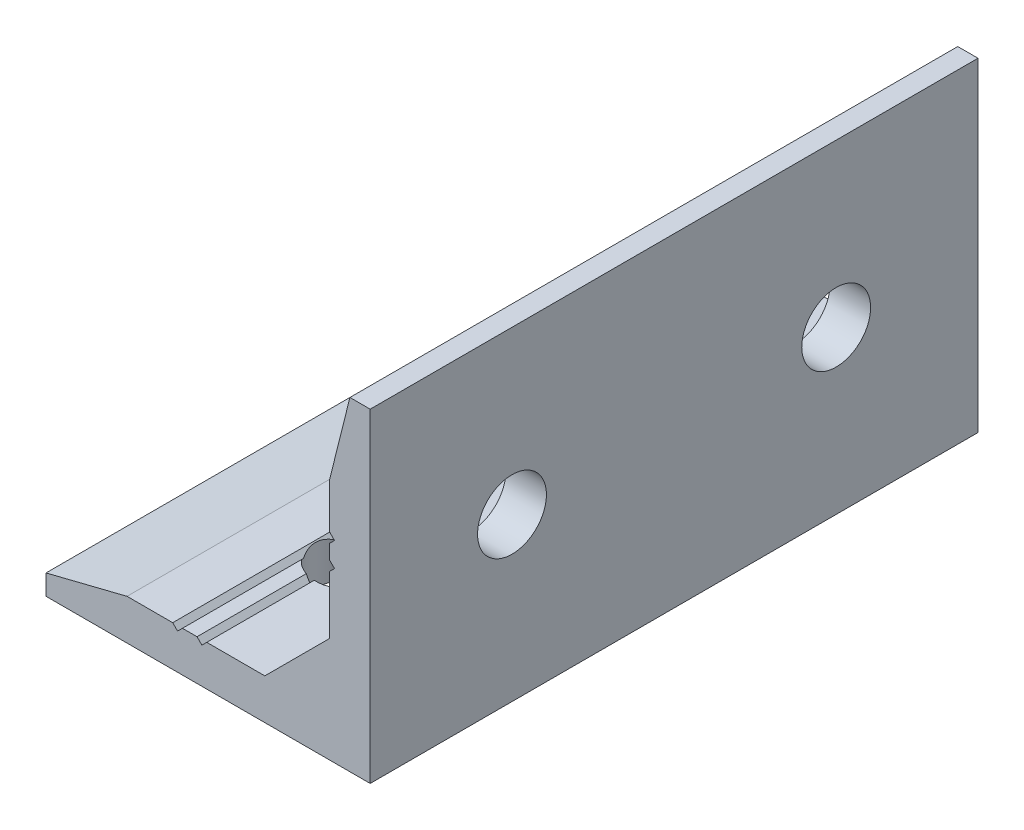
SolidWorks part; units mm, degrees
ref_plane "前视基准面" through (0, 0, 0) normal (0, 0, 1) x (1, 0, 0)
ref_plane "上视基准面" through (0, 0, 0) normal (0, 1, 0) x (1, 0, 0)
ref_plane "右视基准面" through (0, 0, 0) normal (1, 0, 0) x (0, 0, -1)
sketch "草图1" plane through (0, 0, 0) normal (0, 0, 1) x (1, 0, 0)
  line B0 (0, 0) -> (40, 0)
  line B1 (40, 0) -> (40, 40)
  line B2 (10, 5) -> (15.635, 5)
  line B3 (16.835, 5) -> (18.635, 5)
  line B4 (19.835, 5) -> (27, 5)
  line B5 (35, 13) -> (35, 20.165)
  line B6 (35, 21.365) -> (35, 23.165)
  line B7 (35, 24.365) -> (35, 30)
  line B8 (0, 2.5) -> (0, 0)
  line B9 (37.5, 40) -> (40, 40)
  line B10 (0, 2.5) -> (10, 5)
  line B11 (37.5, 40) -> (35, 30)
  line B12 (27, 5) -> (35, 13)
  line B13 (16.235, 4.4) -> (15.635, 5)
  line B14 (16.235, 4.4) -> (16.835, 5)
  line B15 (19.235, 4.4) -> (18.635, 5)
  line B16 (19.235, 4.4) -> (19.835, 5)
  line B17 (35.6, 23.765) -> (35, 24.365)
  line B18 (35.6, 23.765) -> (35, 23.165)
  line B19 (35.6, 20.765) -> (35, 21.365)
  line B20 (35.6, 20.765) -> (35, 20.165)
sketch_block_instance "A$C2EE5613F-1"
sketch_block "A$C2EE5613F"
extrude "凸台-拉伸1" add sketch "草图1" along normal mid plane 75
sketch "草图3" plane through (0, 5, 0) normal (0, 1, 0) x (1, 0, 0)
  line L0 (0, -37.5) -> (0, 37.5) construction
  line L1 (0, 0) -> (13.7586, 0) construction
  circle A0 centre (20, 20) radius 4.25
  circle A1 centre (20, -20) radius 4.25
  dimension "D1" = 20
  dimension "D2" = 20
extrude "切除-拉伸1" cut sketch "草图3" against normal through all
sketch "草图4" plane through (11, -11, 0) normal (-0.7071, 0.7071, 0) x (0, 0, 1)
  line L0 (-37.5, 28.2843) -> (37.5, 28.2843) construction
  line L1 (-37.5, 33.9411) -> (-37.5, 22.6274) construction
  line L2 (37.5, 33.9411) -> (37.5, 22.6274) construction
ref_plane "基准面2" through (20, 20, 0) normal (0.7071, 0.7071, 0) x (0.7071, -0.7071, 0)
mirror "镜向1" about plane through (20, 20, 0) normal (0.7071, 0.7071, 0) of "切除-拉伸1"
